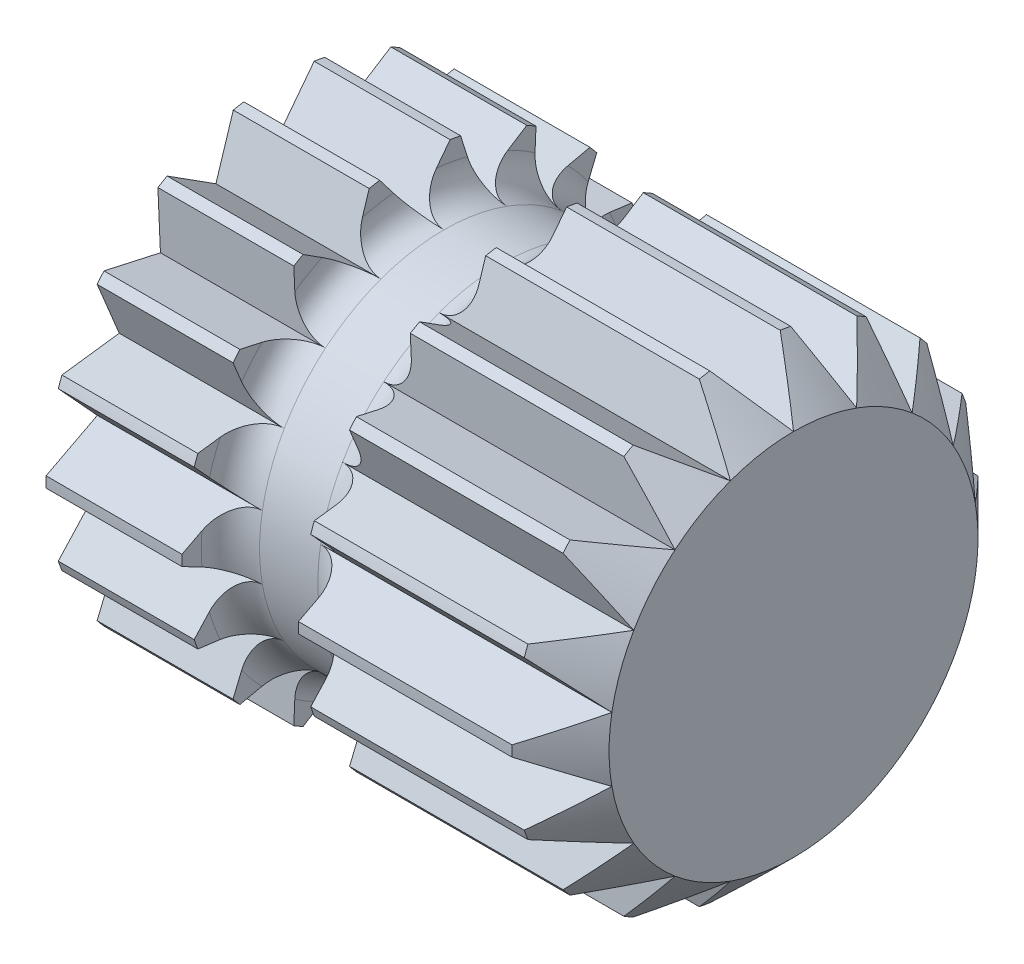
SolidWorks part; units mm, degrees
material "Пруток ДКРВМ 4 НД ЛС59-1 ГОСТ 2060-2006"
ref_plane "Спереди" through (0, 0, 0) normal (0, 0, 1) x (1, 0, 0)
ref_plane "Сверху" through (0, 0, 0) normal (0, 1, 0) x (1, 0, 0)
ref_plane "Справа" through (0, 0, 0) normal (1, 0, 0) x (0, 0, -1)
sketch "Эскиз1" plane through (0, 0, 0) normal (0, 0, 1) x (1, 0, 0)
  line L0 (0, 0) -> (3, 0) construction
  line L1 (0, 2.4) -> (1.4, 2.4)
  line L2 (1.4, 2.4) -> (1.4, 2.2)
  line L3 (1.7, 1.9) -> (2.3, 1.9)
  line L4 (2.6, 2.2) -> (2.6, 2.4)
  line L5 (2.6, 2.4) -> (4.8, 2.4)
  line L6 (4.8, 2.4) -> (5.3, 1.9)
  line L7 (5.3, 1.9) -> (5.3, 0)
  line L8 (5.3, 0) -> (3, 0)
  line L9 (3, 0) -> (3, 1)
  line L10 (3, 1) -> (0, 1)
  line L11 (0, 1) -> (0, 2.4)
  arc A0 (2.6, 2.2) -> (2.3, 1.9) centre (2.3, 2.2) cw
  arc A1 (1.7, 1.9) -> (1.4, 2.2) centre (1.7, 2.2) cw
  dimension "D8" = 0.3
  dimension "D1" = 3.8
  dimension "D2" = 5.3
  dimension "D3" = 0.5
  dimension "D4" = 45
  dimension "D5" = 3.8
  dimension "D6" = 1.4
  dimension "D7" = 1.2
  dimension "D9" = 2
  dimension "D10" = 3
revolve "Повернуть1" add sketch "Эскиз1" angle 360 about L0
hole_wizard "Отверстие обработанное метчиком M31" positions "Эскиз2" profile "Эскиз3" tap size "M3" standard "GOST"
sketch "Эскиз2" plane through (0, 0, 0) normal (-1, 0, 0) x (0, 0, 1)
  point P0 (0, 0)
sketch "Эскиз3" plane through (0, 0, 0) normal (0, 1, 0) x (0, 0, 1)
  line L0 (0, 0) -> (0, 5.2511)
  line L1 (0, 5.2511) -> (1.25, 4.5)
  line L2 (1.25, 4.5) -> (1.25, 0)
  line L5 (1.25, 0) -> (0, 0)
  line L10 (0, 5.2511) -> (-1.25, 4.5) construction
  line L11 (0, -6.35) -> (0, 107.95) construction
  dimension "Диаметр сверла" = 2.5
  dimension "Глубина сверла" = 4.5
  dimension "Угол заточки сверла" = 118
cosmetic thread "Отверстие резьбы1" parameters "D1"=4, "D2"=3
chamfer "Фаска1" distance 0.5 angle 45
sketch "Эскиз4" plane through (0, 0, 0) normal (-1, 0, 0) x (0, 0, 1)
  line L0 (-0.3837, 2.4) -> (0, 1.9)
  line L1 (0, 1.9) -> (0.3837, 2.4)
  line L2 (0.3837, 2.4) -> (-0.3837, 2.4)
  line L3 (0, 1.9) -> (0, 0) construction
  circle A0 centre (0, 0) radius 2.4 construction
  dimension "D1" = 75
  dimension "D2" = 1.9
extrude "Вырез-Вытянуть1" cut sketch "Эскиз4" against normal through all
pattern_circular "Круговой массив1" count 18 over 360 about axis through (0, 0, 0) along (1, 0, 0) of "Вырез-Вытянуть1"
